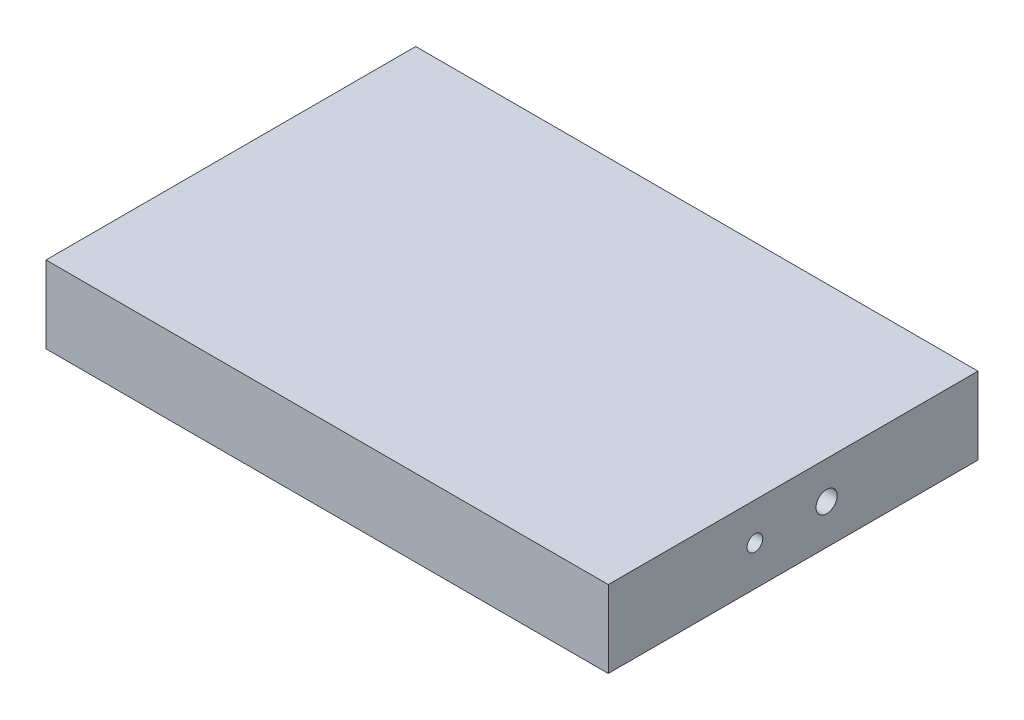
SolidWorks part; units mm, degrees
ref_plane "Front Plane" through (0, 0, 0) normal (0, 0, 1) x (1, 0, 0)
ref_plane "Top Plane" through (0, 0, 0) normal (0, 1, 0) x (1, 0, 0)
ref_plane "Right Plane" through (0, 0, 0) normal (1, 0, 0) x (0, 0, -1)
sketch "Sketch1" plane through (0, 0, 0) normal (0, 1, 0) x (1, 0, 0)
  line L1 (0, 0) -> (36.5, 0)
  line L2 (0, 0) -> (0, 24)
  line L3 (0, 24) -> (36.5, 24)
  line L4 (36.5, 0) -> (36.5, 24)
  dimension "D1" = 36.5
  dimension "D2" = 24
extrude "Boss-Extrude1" add sketch "Sketch1" along normal blind 5
sketch "Sketch2" plane through (36.5, 0, 0) normal (1, 0, 0) x (0, 0, -1)
  circle A0 centre (9.5182, 2.5797) radius 0.5117
  circle A1 centre (14.1701, 2.5797) radius 0.684
extrude "Cut-Extrude1" cut sketch "Sketch2" against normal blind 5.5
